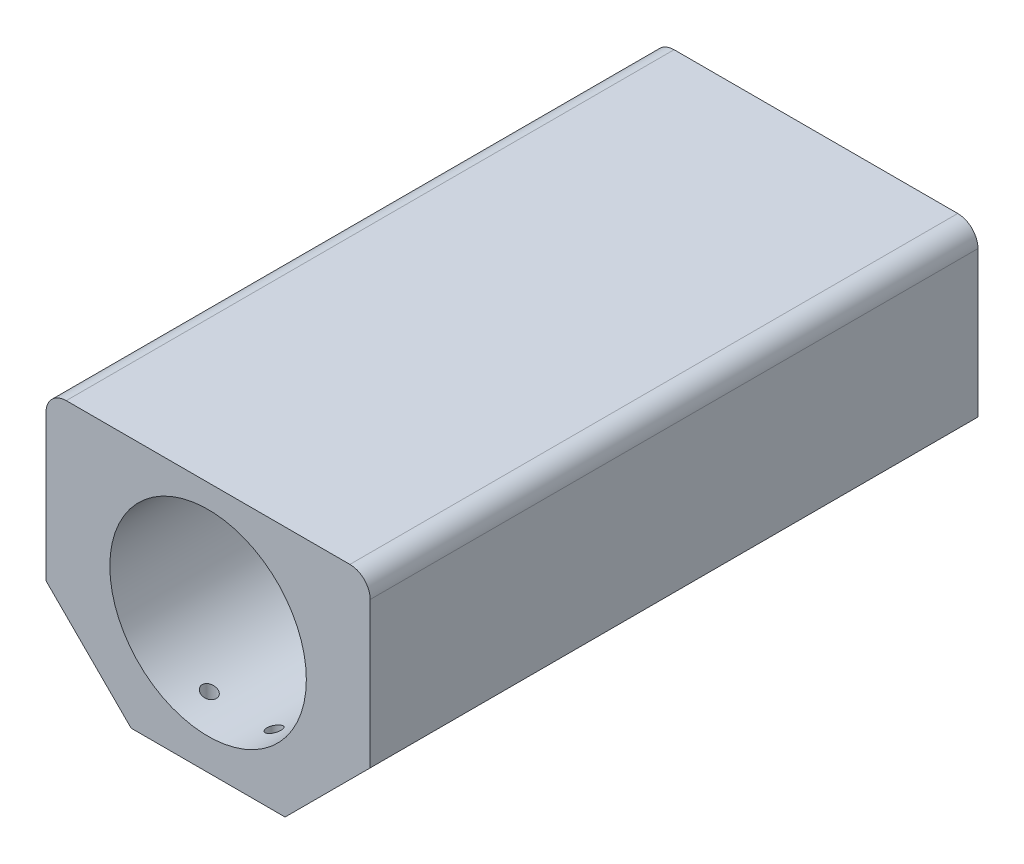
SolidWorks part; units mm, degrees
ref_plane "Front Plane" through (0, 0, 0) normal (0, 0, 1) x (1, 0, 0)
ref_plane "Top Plane" through (0, 0, 0) normal (0, 1, 0) x (1, 0, 0)
ref_plane "Right Plane" through (0, 0, 0) normal (1, 0, 0) x (0, 0, -1)
sketch "Sketch1" plane through (0, 0, 0) normal (0, 0, 1) x (1, 0, 0)
  line L1 (-40, 30) -> (40, 30)
  line L2 (-40, 30) -> (-40, -30)
  line L3 (-40, -30) -> (40, -30)
  line L4 (40, 30) -> (40, -30)
  circle A0 centre (0, 0) radius 24.25
  dimension "D5" = 48.5
  dimension "D1" = 60
  dimension "D2" = 80
  dimension "D3" = 40
  dimension "D4" = 30
extrude "Boss-Extrude1" add sketch "Sketch1" along normal blind 150
sketch "Sketch2" plane through (0, -30, 0) normal (0, -1, 0) x (1, 0, 0)
  line L1 (-40, 150) -> (40, 150)
  line L2 (-40, 150) -> (-40, 0)
  line L3 (-40, 0) -> (40, 0)
  line L4 (40, 150) -> (40, 0)
extrude "Boss-Extrude2" add sketch "Sketch2" along normal blind 2
sketch "Sketch3" plane through (0, 0, 150) normal (0, 0, 1) x (1, 0, 0)
  line L0 (-40, -11) -> (-40, -32)
  line L1 (-40, 30) -> (-40, -32) construction
  line L2 (-40, -32) -> (-19, -32)
  line L3 (40, -32) -> (-40, -32) construction
  line L4 (-19, -32) -> (-40, -11)
  line L5 (0, 0) -> (0, -28.2756) construction
  line L6 (19, -32) -> (40, -11)
  line L7 (40, -32) -> (19, -32)
  line L8 (40, -11) -> (40, -32)
  dimension "D1" = 21
  dimension "D2" = 21
extrude "Cut-Extrude1" cut sketch "Sketch3" against normal through all
sketch "Sketch4" plane through (40, 0, 0) normal (1, 0, 0) x (0, 0, -1)
  line L0 (0, -32) -> (-150, -32) construction
  line L1 (-150, -11) -> (-150, -32) construction
  circle A0 centre (-123, -29) radius 2.1
  dimension "D1" = 4.2
  dimension "D2" = 3
  dimension "D3" = 27
extrude "Cut-Extrude2" cut sketch "Sketch4" against normal blind 24
sketch "Sketch5" plane through (-40, 0, 0) normal (-1, 0, 0) x (0, 0, 1)
  line L0 (0, -32) -> (150, -32) construction
  line L1 (150, -32) -> (150, -11) construction
  circle A0 centre (123, -29) radius 2.1
  dimension "D1" = 4.2
  dimension "D2" = 3
  dimension "D3" = 27
extrude "Cut-Extrude3" cut sketch "Sketch5" against normal blind 24
sketch "Sketch6" plane through (0, -32, 0) normal (0, -1, 0) x (1, 0, 0)
  line L0 (19, 150) -> (-19, 150) construction
  line L1 (-19, 0) -> (-19, 150) construction
  line L2 (0, 0) -> (0, 150) construction
  circle A0 centre (-8, 141.7) radius 1.75
  circle A1 centre (-8, 111.7) radius 1.75
  circle A2 centre (8, 111.7) radius 1.75
  circle A3 centre (8, 141.7) radius 1.75
  dimension "D1" = 3.5
  dimension "D2" = 3.5
  dimension "D3" = 8.3
  dimension "D4" = 38.3
  dimension "D5" = 11
  dimension "D6" = 11
extrude "Cut-Extrude4" cut sketch "Sketch6" against normal up to next
fillet "Fillet1" radius 5 2 edges at (40, 30, 75) (-40, 30, 75)
